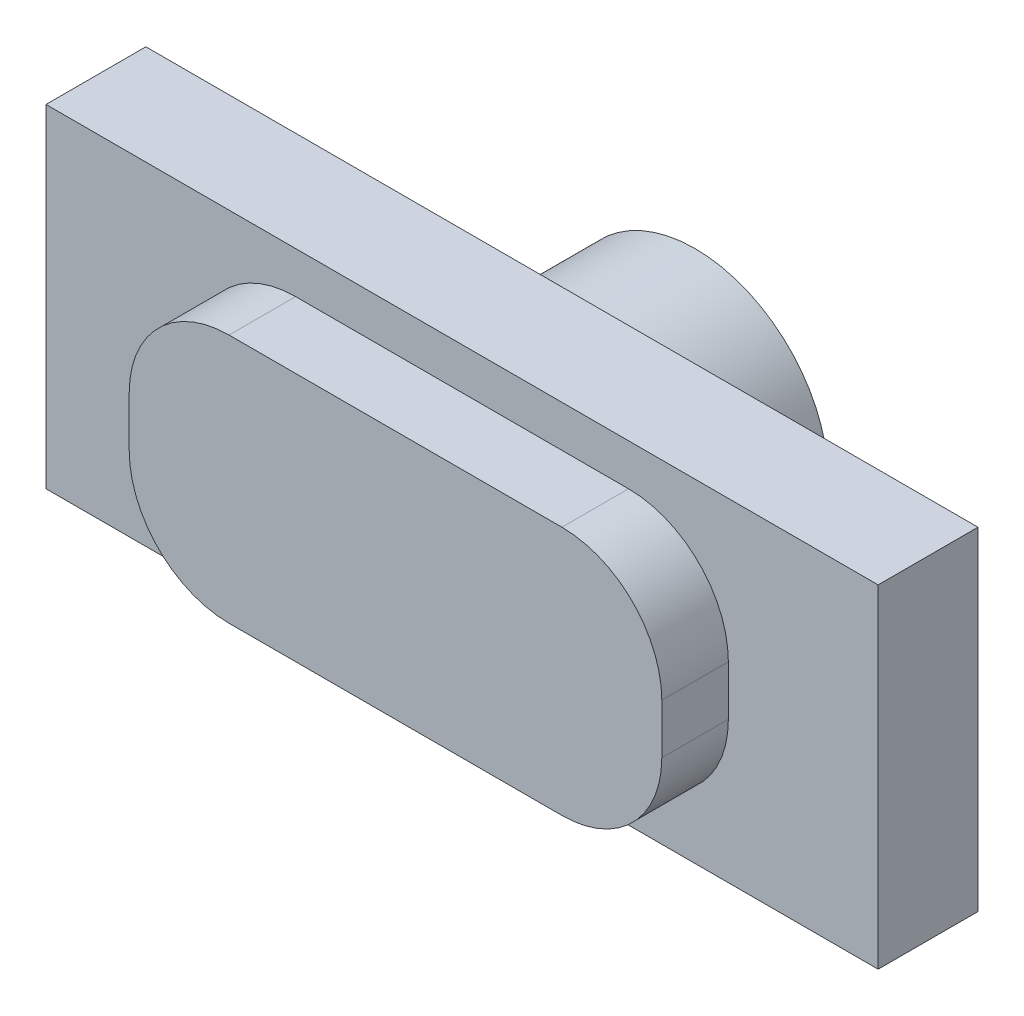
SolidWorks part; units mm, degrees
ref_plane "Přední rovina" through (0, 0, 0) normal (0, 0, 1) x (1, 0, 0)
ref_plane "Horní rovina" through (0, 0, 0) normal (0, 1, 0) x (1, 0, 0)
ref_plane "Pravá rovina" through (0, 0, 0) normal (1, 0, 0) x (0, 0, -1)
sketch "Skica1" plane through (0, 0, 0) normal (0, 0, 1) x (1, 0, 0)
  line L1 (-12.5, 5) -> (12.5, 5)
  line L2 (-12.5, 5) -> (-12.5, -5)
  line L3 (-12.5, -5) -> (12.5, -5)
  line L4 (12.5, 5) -> (12.5, -5)
  line L5 (-12.5, 5) -> (12.5, -5) construction
  line L6 (-12.5, -5) -> (12.5, 5) construction
  point P0 (0, 0)
  dimension "D1" = 25
  dimension "D2" = 10
extrude "Přidat vysunutím1" add sketch "Skica1" along normal blind 3
sketch "Skica2" plane through (0, 0, 3) normal (0, 0, 1) x (1, 0, 0)
  line L1 (-5, 3.75) -> (5, 3.75)
  line L2 (-8, 0.75) -> (-8, -0.75)
  line L3 (-5, -3.75) -> (5, -3.75)
  line L4 (8, 0.75) -> (8, -0.75)
  line L5 (-8, 3.75) -> (8, -3.75) construction
  line L6 (-8, -3.75) -> (8, 3.75) construction
  arc A0 (5, -3.75) -> (8, -0.75) centre (5, -0.75) ccw
  arc A1 (5, 3.75) -> (8, 0.75) centre (5, 0.75) cw
  arc A2 (-5, 3.75) -> (-8, 0.75) centre (-5, 0.75) ccw
  arc A3 (-8, -0.75) -> (-5, -3.75) centre (-5, -0.75) ccw
  point P0 (0, 0)
  dimension "D3" = 3
  dimension "D1" = 16
  dimension "D2" = 7.5
extrude "Přidat vysunutím2" add sketch "Skica2" along normal blind 2
sketch "Skica3" plane through (0, 0, 0) normal (0, 0, -1) x (-1, 0, 0)
  line L0 (4.6757, -0.5) -> (-5.7172, -0.5)
  line L1 (0, 0) -> (-1.1625, 0)
  line L2 (4.6757, 0.5) -> (-5.7172, 0.5)
  circle A0 centre (0, 0) radius 4
  dimension "D1" = 8
  dimension "D2" = 0.5
extrude "Přidat vysunutím3" add sketch "Skica3" along normal blind 4 contours L2 A0 | L0 A0
sketch "Skica4" plane through (0, 0, -4) normal (0, 0, -1) x (-1, 0, 0)
  circle A0 centre (0, 0) radius 2.6
  dimension "D1" = 5.2
extrude "Odebrat vysunutím1" cut sketch "Skica4" against normal blind 8.7
